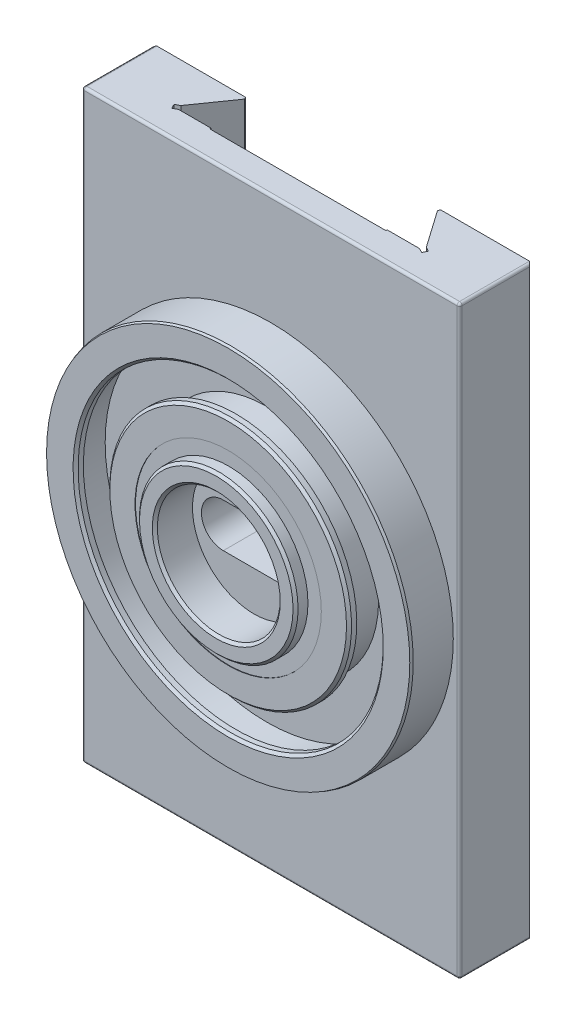
SolidWorks part; units mm, degrees
material "Plain Carbon Steel"
ref_plane "Front Plane" through (0, 0, 0) normal (0, 0, 1) x (1, 0, 0)
ref_plane "Top Plane" through (0, 0, 0) normal (0, 1, 0) x (1, 0, 0)
ref_plane "Right Plane" through (0, 0, 0) normal (1, 0, 0) x (0, 0, -1)
sketch "Sketch1" plane through (0, 0, 0) normal (0, 1, 0) x (1, 0, 0)
  line L0 (-95.25, 0) -> (95.25, 0)
  line L1 (95.25, 0) -> (95.25, 36.5125)
  line L2 (95.25, 36.5125) -> (47.9379, 36.5125)
  line L3 (47.9379, 36.5125) -> (63.5, 14.2875)
  line L4 (63.5, 14.2875) -> (44.45, 14.2875)
  line L5 (-63.5, 14.2875) -> (-47.9379, 36.5125)
  line L6 (-47.9379, 36.5125) -> (-95.25, 36.5125)
  line L7 (-95.25, 36.5125) -> (-95.25, 0)
  line L8 (0, 0) -> (0, 55.3244) construction
  line L9 (-44.45, 13.6525) -> (44.45, 13.6525)
  line L10 (44.45, 13.6525) -> (44.45, 14.2875)
  line L11 (-44.45, 13.6525) -> (-44.45, 14.2875)
  line L12 (-44.45, 14.2875) -> (-63.5, 14.2875)
  point P4 (0, 0)
  point P17 (0, 13.6525)
  dimension "D1" = 55
  dimension "D2" = 190.5
  dimension "D3" = 127
  dimension "D4" = 22.225
  dimension "D5" = 36.5125
  dimension "D6" = 88.9
  dimension "D7" = 0.635
extrude "Boss-Extrude1" add sketch "Sketch1" along normal mid plane 295.275 contours L7 L0 L1 L2 L3 L4 L5 L6
sketch "Sketch3" plane through (0, 147.6375, 0) normal (0, 1, 0) x (1, 0, 0)
  line L0 (-63.5, 14.2875) -> (-42.0218, 25.4684) construction
  line L1 (-63.5, 14.2875) -> (-47.9379, 36.5125) construction
  line L2 (-44.45, 14.2875) -> (-63.5, 14.2875) construction
  line L3 (63.5, 14.2875) -> (32.3008, 30.5288) construction
  line L4 (63.5, 14.2875) -> (44.45, 14.2875) construction
  line L5 (47.9379, 36.5125) -> (63.5, 14.2875) construction
  line L6 (-61.9224, 16.5405) -> (-64.1754, 15.3677)
  line L7 (-61.9224, 16.5405) -> (-60.7496, 14.2875)
  line L8 (-64.1754, 15.3677) -> (-63.0026, 13.1147)
  line L9 (-60.7496, 14.2875) -> (-63.0026, 13.1147)
  line L10 (-61.9224, 16.5405) -> (-63.0026, 13.1147) construction
  line L11 (-64.1754, 15.3677) -> (-60.7496, 14.2875) construction
  line L12 (64.1754, 15.3677) -> (61.9224, 16.5405)
  line L13 (64.1754, 15.3677) -> (63.0026, 13.1147)
  line L14 (61.9224, 16.5405) -> (60.7496, 14.2875)
  line L15 (63.0026, 13.1147) -> (60.7496, 14.2875)
  line L16 (64.1754, 15.3677) -> (60.7496, 14.2875) construction
  line L17 (61.9224, 16.5405) -> (63.0026, 13.1147) construction
  point P15 (-62.4625, 14.8276)
  point P16 (62.4625, 14.8276)
  dimension "D1" = 2.54
  dimension "D2" = 2.54
extrude "Cut-Extrude1" cut sketch "Sketch3" against normal through all
sketch "Sketch2" plane through (0, 0, 0) normal (0, 0, 1) x (1, 0, 0)
  circle A0 centre (0, 0) radius 92.075
  dimension "D1" = 184.15
extrude "Boss-Extrude2" add sketch "Sketch2" along normal offset from surface (21.4875 mm away) 58 up to face at (71.5939, 0, -36.5125)
sketch "Sketch4" plane through (0, 0, 0) normal (1, 0, 0) x (0, 0, -1)
  line L0 (0, 0) -> (-105.4021, 0) construction
  line L1 (-28.0644, 76.96) -> (-17.5644, 76.96)
  line L3 (-17.5644, 76.96) -> (-17.5644, 81.46)
  line L4 (-17.5644, 81.46) -> (-2.0644, 81.46)
  line L5 (-2.0644, 81.46) -> (-2.0644, 56.46)
  line L6 (-2.0644, 56.46) -> (-17.5644, 56.46)
  line L7 (-17.5644, 56.46) -> (-17.5644, 60.96)
  line L8 (-17.5644, 60.96) -> (-28.0644, 60.96)
  line L9 (-28.0644, 60.96) -> (-28.0644, 76.96)
  line L10 (-28.0644, 68.96) -> (-2.0644, 68.96) construction
  dimension "D1" = 26
  dimension "D2" = 16
  dimension "D3" = 25
  dimension "D4" = 10.5
  dimension "D5" = 121.92
revolve "Cut-Revolve1" cut sketch "Sketch4" angle 360 about L0
sketch "Sketch5" plane through (0, 0, 21.4875) normal (0, 0, 1) x (1, 0, 0)
  circle A0 centre (0, 0) radius 40
  dimension "D1" = 80
extrude "Boss-Extrude3" add sketch "Sketch5" along normal blind 6
sketch "Sketch8" plane through (0, 0, 21.4875) normal (0, 0, 1) x (1, 0, 0)
  circle A0 centre (0, 0) radius 40
  circle A1 centre (0, 0) radius 46.99
  circle A3 centre (0, 0) radius 40 construction
  dimension "D1" = 93.98
extrude "Cut-Extrude4" cut sketch "Sketch8" against normal blind 0.254
sketch "Sketch6" plane through (0, 0, 27.4875) normal (0, 0, 1) x (1, 0, 0)
  circle A0 centre (0, 0) radius 31
  dimension "D1" = 62
extrude "Cut-Extrude2" cut sketch "Sketch6" against normal blind 19
sketch "Sketch7" plane through (0, 0, 8.4875) normal (0, 0, 1) x (1, 0, 0)
  line L0 (15.45, 0) -> (-15.45, 0) construction
  line L1 (15.45, -11.05) -> (-15.45, -11.05)
  line L2 (15.45, 11.05) -> (-15.45, 11.05)
  arc A0 (15.45, -11.05) -> (15.45, 11.05) centre (15.45, 0) ccw
  arc A1 (-15.45, 11.05) -> (-15.45, -11.05) centre (-15.45, 0) ccw
  point P2 (0, 0)
  dimension "D2" = 53
  dimension "D1" = 22.1
extrude "Cut-Extrude3" cut sketch "Sketch7" against normal blind 38.1
chamfer "Chamfer3" distance 1.27 angle 45 2 edges at (95.25, 0, -36.5125) (-95.25, 0, -36.5125)
chamfer "Chamfer1" distance 1.27 angle 65 2 edges at (47.9379, 0, -36.5125) (-47.9379, 0, -36.5125)
fillet "Fillet1" radius 1.27 8 edges at (95.25, -147.6375, -17.6212) (-95.25, -147.6375, -17.6212) (0, -147.6375, 0) (95.25, 0, 0) (95.25, 147.6375, -17.6212) (-95.25, 147.6375, -17.6212) (0, 147.6375, 0) (-95.25, 0, 0)
chamfer "Chamfer2" distance 1.27 angle 20 1 edges at (92.075, 0, 21.4875)
chamfer "Chamfer4" distance 1.27 angle 45 4 edges at (31, 0, 27.4875) (40, 0, 27.4875) (60.96, 0, 21.4875) (76.96, 0, 21.4875)
